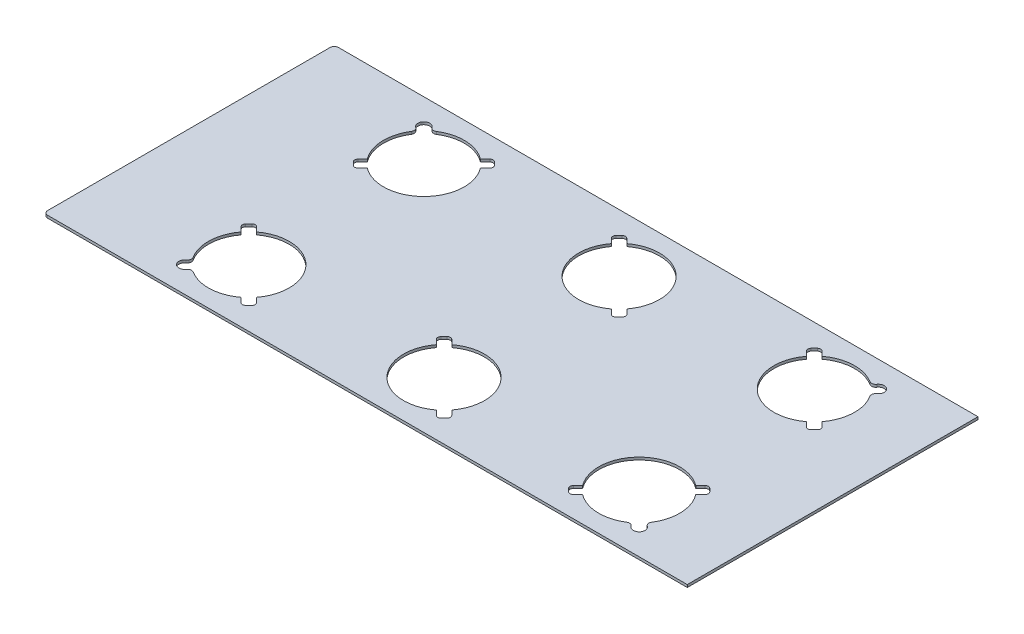
SolidWorks part; units mm, degrees
material "Hexcel AS4C (3000 Filaments)"
ref_plane "Front" through (0, 0, 0) normal (0, 0, 1) x (1, 0, 0)
ref_plane "Top" through (0, 0, 0) normal (0, 1, 0) x (1, 0, 0)
ref_plane "Right" through (0, 0, 0) normal (1, 0, 0) x (0, 0, -1)
sketch "Sketch1" plane through (0, 0, 0) normal (0, 1, 0) x (1, 0, 0)
  line L1 (-184.15, -88.9) -> (184.15, -88.9)
  line L2 (-184.15, -88.9) -> (-184.15, 88.9)
  line L3 (-184.15, 88.9) -> (184.15, 88.9)
  line L4 (184.15, -88.9) -> (184.15, 88.9)
  line L5 (-184.15, -88.9) -> (184.15, 88.9) construction
  line L6 (-184.15, 88.9) -> (184.15, -88.9) construction
  point P0 (0, 0)
  dimension "D1" = 368.3
  dimension "D2" = 177.8
extrude "Boss-Extrude1" add sketch "Sketch1" along normal blind 1.5748
sketch "Sketch2" plane through (-184.15, 0, 0) normal (-1, 0, 0) x (0, 0, 1)
  line L1 (88.9, 0) -> (-88.9, 0)
  line L2 (88.9, 0) -> (88.9, 1.5748)
  line L3 (88.9, 1.5748) -> (-88.9, 1.5748)
  line L4 (-88.9, 0) -> (-88.9, 1.5748)
extrude "Boss-Extrude2" add sketch "Sketch2" along normal blind 25.4
sketch "Sketch3" plane through (0, 0, 0) normal (0, -1, 0) x (1, 0, 0)
  line L0 (96.8413, -71.3316) -> (99.493, -68.6799) construction
  line L1 (141.9187, -35.7294) -> (139.267, -38.3811) construction
  line L2 (140.0095, -30.9918) -> (141.9187, -32.901) construction
  line L3 (134.5294, -33.6435) -> (137.1811, -30.9918) construction
  line L4 (104.2306, -73.4175) -> (101.5789, -76.0692) construction
  line L5 (98.7505, -76.0692) -> (96.8413, -74.16) construction
  line L6 (141.9187, -35.7294) -> (139.054, -38.5941)
  line L7 (140.0095, -30.9918) -> (141.9187, -32.901)
  line L8 (134.3164, -33.8565) -> (137.1811, -30.9918)
  line L9 (104.4436, -73.2045) -> (101.5789, -76.0692)
  line L10 (98.7505, -76.0692) -> (96.8413, -74.16)
  line L11 (96.8413, -71.3316) -> (99.706, -68.4669)
  line L12 (22.5387, -35.7294) -> (19.887, -38.3811) construction
  line L13 (20.6295, -30.9918) -> (22.5387, -32.901) construction
  line L14 (15.1494, -33.6435) -> (17.8011, -30.9918) construction
  line L15 (-22.5387, -71.3316) -> (-19.887, -68.6799) construction
  line L16 (-20.6295, -76.0692) -> (-22.5387, -74.16) construction
  line L17 (-15.1494, -73.4175) -> (-17.8011, -76.0692) construction
  line L18 (22.5387, -35.7294) -> (19.674, -38.5941)
  line L19 (20.6295, -30.9918) -> (22.5387, -32.901)
  line L20 (14.9364, -33.8565) -> (17.8011, -30.9918)
  line L21 (-22.5387, -71.3316) -> (-19.674, -68.4669)
  line L22 (-20.6295, -76.0692) -> (-22.5387, -74.16)
  line L23 (-14.9364, -73.2045) -> (-17.8011, -76.0692)
  line L24 (-137.1811, -30.9918) -> (-134.5294, -33.6435) construction
  line L25 (-141.9187, -32.901) -> (-140.0095, -30.9918) construction
  line L26 (-139.267, -38.3811) -> (-141.9187, -35.7294) construction
  line L27 (-99.493, -68.6799) -> (-96.8413, -71.3316) construction
  line L28 (-96.8413, -74.16) -> (-98.7505, -76.0692) construction
  line L29 (-101.5789, -76.0692) -> (-104.2306, -73.4175) construction
  line L30 (-137.1811, -30.9918) -> (-134.3164, -33.8565)
  line L31 (-141.9187, -32.901) -> (-140.0095, -30.9918)
  line L32 (-139.054, -38.5941) -> (-141.9187, -35.7294)
  line L33 (-99.706, -68.4669) -> (-96.8413, -71.3316)
  line L34 (-96.8413, -74.16) -> (-98.7505, -76.0692)
  line L35 (-101.5789, -76.0692) -> (-104.4436, -73.2045)
  line L36 (-134.5294, 33.6435) -> (-137.1811, 30.9918) construction
  line L37 (-140.0095, 30.9918) -> (-141.9187, 32.901) construction
  line L38 (-141.9187, 35.7294) -> (-139.267, 38.3811) construction
  line L39 (-96.8413, 71.3316) -> (-99.493, 68.6799) construction
  line L40 (-98.7505, 76.0692) -> (-96.8413, 74.16) construction
  line L41 (-104.2306, 73.4175) -> (-101.5789, 76.0692) construction
  line L42 (-134.3164, 33.8565) -> (-137.1811, 30.9918)
  line L43 (-140.0095, 30.9918) -> (-141.9187, 32.901)
  line L44 (-141.9187, 35.7294) -> (-139.054, 38.5941)
  line L45 (-96.8413, 71.3316) -> (-99.706, 68.4669)
  line L46 (-98.7505, 76.0692) -> (-96.8413, 74.16)
  line L47 (-104.4436, 73.2045) -> (-101.5789, 76.0692)
  line L48 (15.1494, 73.4175) -> (17.8011, 76.0692) construction
  line L49 (20.6295, 76.0692) -> (22.5387, 74.16) construction
  line L50 (22.5387, 71.3316) -> (19.887, 68.6799) construction
  line L51 (-20.6295, 30.9918) -> (-22.5387, 32.901) construction
  line L52 (-15.1494, 33.6435) -> (-17.8011, 30.9918) construction
  line L53 (-22.5387, 35.7294) -> (-19.887, 38.3811) construction
  line L54 (14.9364, 73.2045) -> (17.8011, 76.0692)
  line L55 (20.6295, 76.0692) -> (22.5387, 74.16)
  line L56 (22.5387, 71.3316) -> (19.674, 68.4669)
  line L57 (-20.6295, 30.9918) -> (-22.5387, 32.901)
  line L58 (-14.9364, 33.8565) -> (-17.8011, 30.9918)
  line L59 (-22.5387, 35.7294) -> (-19.674, 38.5941)
  line L60 (101.5789, 76.0692) -> (104.2306, 73.4175) construction
  line L61 (96.8413, 74.16) -> (98.7505, 76.0692) construction
  line L62 (99.493, 68.6799) -> (96.8413, 71.3316) construction
  line L63 (139.267, 38.3811) -> (141.9187, 35.7294) construction
  line L64 (141.9187, 32.901) -> (140.0095, 30.9918) construction
  line L65 (137.1811, 30.9918) -> (134.5294, 33.6435) construction
  line L66 (101.5789, 76.0692) -> (104.4436, 73.2045)
  line L67 (96.8413, 74.16) -> (98.7505, 76.0692)
  line L68 (99.706, 68.4669) -> (96.8413, 71.3316)
  line L69 (139.054, 38.5941) -> (141.9187, 35.7294)
  line L70 (141.9187, 32.901) -> (140.0095, 30.9918)
  line L71 (137.1811, 30.9918) -> (134.3164, 33.8565)
  arc A0 (104.4436, -73.2045) -> (139.054, -38.5941) centre (119.38, -53.5305) ccw
  arc A2 (-14.9364, -73.2045) -> (19.674, -38.5941) centre (0, -53.5305) ccw
  arc A3 (-99.706, -68.4669) -> (-134.3164, -33.8565) centre (-119.38, -53.5305) ccw
  arc A4 (-134.3164, 33.8565) -> (-99.706, 68.4669) centre (-119.38, 53.5305) ccw
  arc A5 (-14.9364, 33.8565) -> (19.674, 68.4669) centre (0, 53.5305) ccw
  arc A6 (139.054, 38.5941) -> (104.4436, 73.2045) centre (119.38, 53.5305) ccw
  arc A7 (96.8413, -71.3316) -> (96.8413, -74.16) centre (98.2555, -72.7458) ccw construction
  arc A8 (141.9187, -35.7294) -> (141.9187, -32.901) centre (140.5045, -34.3152) ccw construction
  arc A9 (140.0095, -30.9918) -> (137.1811, -30.9918) centre (138.5953, -32.406) ccw construction
  arc A10 (98.7505, -76.0692) -> (101.5789, -76.0692) centre (100.1647, -74.655) ccw construction
  arc A11 (141.9187, -35.7294) -> (141.9187, -32.901) centre (140.5045, -34.3152) ccw
  arc A12 (140.0095, -30.9918) -> (137.1811, -30.9918) centre (138.5953, -32.406) ccw
  arc A13 (98.7505, -76.0692) -> (101.5789, -76.0692) centre (100.1647, -74.655) ccw
  arc A14 (96.8413, -71.3316) -> (96.8413, -74.16) centre (98.2555, -72.7458) ccw
  arc A15 (134.3164, -33.8565) -> (99.706, -68.4669) centre (119.38, -53.5305) ccw
  arc A16 (22.5387, -35.7294) -> (22.5387, -32.901) centre (21.1245, -34.3152) ccw construction
  arc A17 (20.6295, -30.9918) -> (17.8011, -30.9918) centre (19.2153, -32.406) ccw construction
  arc A18 (-22.5387, -71.3316) -> (-22.5387, -74.16) centre (-21.1245, -72.7458) ccw construction
  arc A19 (-20.6295, -76.0692) -> (-17.8011, -76.0692) centre (-19.2153, -74.655) ccw construction
  arc A20 (22.5387, -35.7294) -> (22.5387, -32.901) centre (21.1245, -34.3152) ccw
  arc A21 (20.6295, -30.9918) -> (17.8011, -30.9918) centre (19.2153, -32.406) ccw
  arc A22 (-22.5387, -71.3316) -> (-22.5387, -74.16) centre (-21.1245, -72.7458) ccw
  arc A23 (-20.6295, -76.0692) -> (-17.8011, -76.0692) centre (-19.2153, -74.655) ccw
  arc A24 (14.9364, -33.8565) -> (-19.674, -68.4669) centre (0, -53.5305) ccw
  arc A25 (-137.1811, -30.9918) -> (-140.0095, -30.9918) centre (-138.5953, -32.406) ccw construction
  arc A26 (-141.9187, -32.901) -> (-141.9187, -35.7294) centre (-140.5045, -34.3152) ccw construction
  arc A27 (-96.8413, -74.16) -> (-96.8413, -71.3316) centre (-98.2555, -72.7458) ccw construction
  arc A28 (-101.5789, -76.0692) -> (-98.7505, -76.0692) centre (-100.1647, -74.655) ccw construction
  arc A29 (-137.1811, -30.9918) -> (-140.0095, -30.9918) centre (-138.5953, -32.406) ccw
  arc A30 (-141.9187, -32.901) -> (-141.9187, -35.7294) centre (-140.5045, -34.3152) ccw
  arc A31 (-96.8413, -74.16) -> (-96.8413, -71.3316) centre (-98.2555, -72.7458) ccw
  arc A32 (-101.5789, -76.0692) -> (-98.7505, -76.0692) centre (-100.1647, -74.655) ccw
  arc A33 (-140.0095, 30.9918) -> (-137.1811, 30.9918) centre (-138.5953, 32.406) ccw construction
  arc A34 (-141.9187, 35.7294) -> (-141.9187, 32.901) centre (-140.5045, 34.3152) ccw construction
  arc A35 (-96.8413, 71.3316) -> (-96.8413, 74.16) centre (-98.2555, 72.7458) ccw construction
  arc A36 (-98.7505, 76.0692) -> (-101.5789, 76.0692) centre (-100.1647, 74.655) ccw construction
  arc A37 (-140.0095, 30.9918) -> (-137.1811, 30.9918) centre (-138.5953, 32.406) ccw
  arc A38 (-141.9187, 35.7294) -> (-141.9187, 32.901) centre (-140.5045, 34.3152) ccw
  arc A39 (-96.8413, 71.3316) -> (-96.8413, 74.16) centre (-98.2555, 72.7458) ccw
  arc A40 (-98.7505, 76.0692) -> (-101.5789, 76.0692) centre (-100.1647, 74.655) ccw
  arc A41 (20.6295, 76.0692) -> (17.8011, 76.0692) centre (19.2153, 74.655) ccw construction
  arc A42 (22.5387, 71.3316) -> (22.5387, 74.16) centre (21.1245, 72.7458) ccw construction
  arc A43 (-22.5387, 35.7294) -> (-22.5387, 32.901) centre (-21.1245, 34.3152) ccw construction
  arc A44 (-20.6295, 30.9918) -> (-17.8011, 30.9918) centre (-19.2153, 32.406) ccw construction
  arc A45 (20.6295, 76.0692) -> (17.8011, 76.0692) centre (19.2153, 74.655) ccw
  arc A46 (22.5387, 71.3316) -> (22.5387, 74.16) centre (21.1245, 72.7458) ccw
  arc A47 (-22.5387, 35.7294) -> (-22.5387, 32.901) centre (-21.1245, 34.3152) ccw
  arc A48 (-20.6295, 30.9918) -> (-17.8011, 30.9918) centre (-19.2153, 32.406) ccw
  arc A49 (101.5789, 76.0692) -> (98.7505, 76.0692) centre (100.1647, 74.655) ccw construction
  arc A50 (96.8413, 74.16) -> (96.8413, 71.3316) centre (98.2555, 72.7458) ccw construction
  arc A51 (141.9187, 32.901) -> (141.9187, 35.7294) centre (140.5045, 34.3152) ccw construction
  arc A52 (137.1811, 30.9918) -> (140.0095, 30.9918) centre (138.5953, 32.406) ccw construction
  arc A53 (101.5789, 76.0692) -> (98.7505, 76.0692) centre (100.1647, 74.655) ccw
  arc A54 (96.8413, 74.16) -> (96.8413, 71.3316) centre (98.2555, 72.7458) ccw
  arc A55 (141.9187, 32.901) -> (141.9187, 35.7294) centre (140.5045, 34.3152) ccw
  arc A56 (137.1811, 30.9918) -> (140.0095, 30.9918) centre (138.5953, 32.406) ccw
  arc A58 (-104.4436, 73.2045) -> (-139.054, 38.5941) centre (-119.38, 53.5305) ccw
  arc A59 (14.9364, 73.2045) -> (-19.674, 38.5941) centre (0, 53.5305) ccw
  arc A60 (99.706, 68.4669) -> (134.3164, 33.8565) centre (119.38, 53.5305) ccw
  arc A61 (-139.054, -38.5941) -> (-104.4436, -73.2045) centre (-119.38, -53.5305) ccw
  dimension "D1" = 24.7015
extrude "Cut-Extrude1" cut sketch "Sketch3" against normal through all
hole_wizard "9/32 (0.28125) Diameter Hole1" positions "Sketch4" profile "Sketch5" hole size "9/32" standard "ANSI Inch" end condition through all
sketch "Sketch4" plane through (0, 0, 0) normal (0, -1, 0) x (-1, 0, 0)
  point P0 (-139.0015, 73.152)
  point P3 (139.0015, 73.152)
  point P6 (139.0015, -73.152)
  point P9 (-139.0015, -73.152)
sketch "Sketch5" plane through (139.0015, 0, -73.152) normal (1, 0, 0) x (0, 0, -1)
  line L0 (0, 0) -> (0, 1.5748)
  line L1 (0, 1.5748) -> (3.5719, 1.5748)
  line L2 (3.5719, 1.5748) -> (3.5719, 0)
  line L5 (3.5719, 0) -> (0, 0)
  line L11 (0, -6.35) -> (0, 107.95) construction
  dimension "Thru Hole Dia." = 7.1437
  dimension "Thru Hole Depth" = 1.5748
fillet "Fillet1" radius 2.54 10 edges at (-209.55, 0.7874, -88.9) (-209.55, 0.7874, 88.9) (-135.5602, 0.7874, 72.195) (-138.0445, 0.7874, 69.7107) (-138.0445, 0.7874, -69.7107) (-135.5602, 0.7874, -72.195) (135.5602, 0.7874, -72.195) (138.0445, 0.7874, -69.7107) (138.0445, 0.7874, 69.7107) (135.5602, 0.7874, 72.195)
